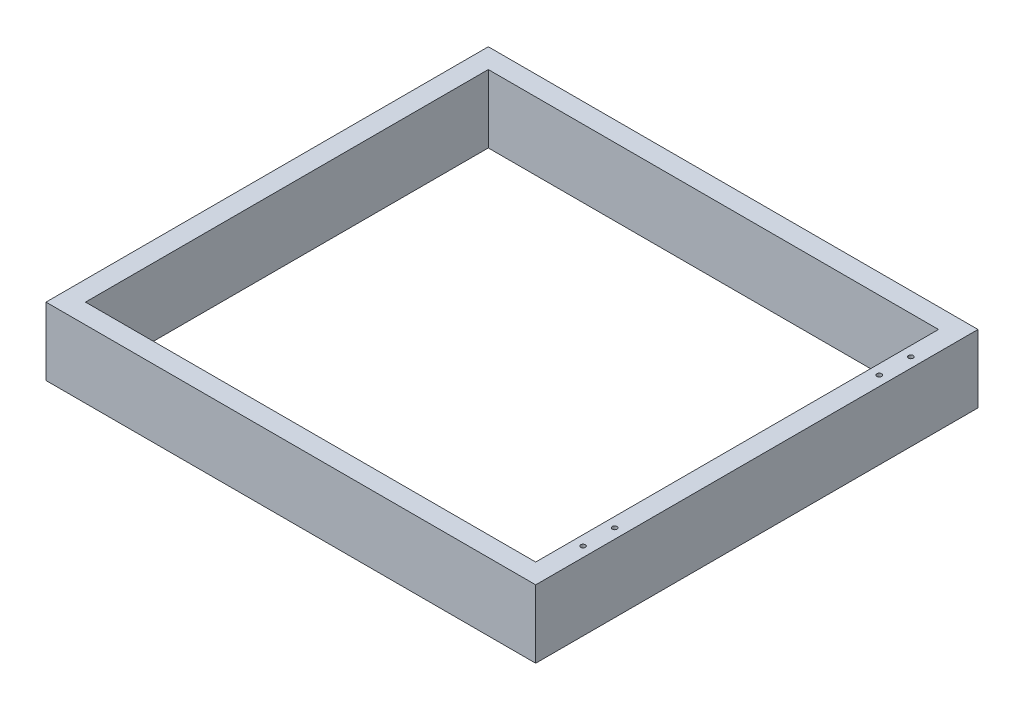
SolidWorks part; units mm, degrees
ref_plane "Front Plane" through (0, 0, 0) normal (0, 0, 1) x (1, 0, 0)
ref_plane "Top Plane" through (0, 0, 0) normal (0, 1, 0) x (1, 0, 0)
ref_plane "Right Plane" through (0, 0, 0) normal (1, 0, 0) x (0, 0, -1)
sketch "Sketch1" plane through (0, 0, 0) normal (0, 1, 0) x (1, 0, 0)
  line L1 (0, 0) -> (310, 0)
  line L2 (0, 0) -> (0, 280)
  line L3 (0, 280) -> (310, 280)
  line L4 (310, 0) -> (310, 280)
  line L5 (12.5, 12.5) -> (297.5, 12.5)
  line L6 (12.5, 12.5) -> (12.5, 267.5)
  line L7 (12.5, 267.5) -> (297.5, 267.5)
  line L8 (297.5, 12.5) -> (297.5, 267.5)
  point P9 (12.5, 140)
  point P10 (0, 140)
  point P11 (155, 12.5)
  point P12 (155, 0)
  dimension "D1" = 310
  dimension "D2" = 280
  dimension "D3" = 255
  dimension "D4" = 285
extrude "Boss-Extrude1" add sketch "Sketch1" along normal blind 43
sketch "Sketch2" plane through (0, 43, 0) normal (0, 1, 0) x (1, 0, 0)
  line L1 (310, 0) -> (310, 280) construction
  line L2 (303.75, 243.75) -> (303.75, 223.75) construction
  line L3 (303.75, 56.25) -> (303.75, 36.25) construction
  line L4 (310, 280) -> (0, 280) construction
  circle A0 centre (303.75, 243.75) radius 1.5
  circle A1 centre (303.75, 223.75) radius 1.5
  circle A2 centre (303.75, 56.25) radius 1.5
  circle A3 centre (303.75, 36.25) radius 1.5
  point P10 (303.75, 233.75)
  point P13 (303.75, 46.25)
  point P15 (303.75, 243.75)
  dimension "D1" = 3
  dimension "D2" = 3
  dimension "D5" = 3
  dimension "D6" = 3
  dimension "D3" = 20
  dimension "D4" = 6.25
  dimension "D7" = 6.25
  dimension "D8" = 20
  dimension "D9" = 46.25
  dimension "D10" = 187.5
extrude "Cut-Extrude1" cut sketch "Sketch2" against normal blind 10
